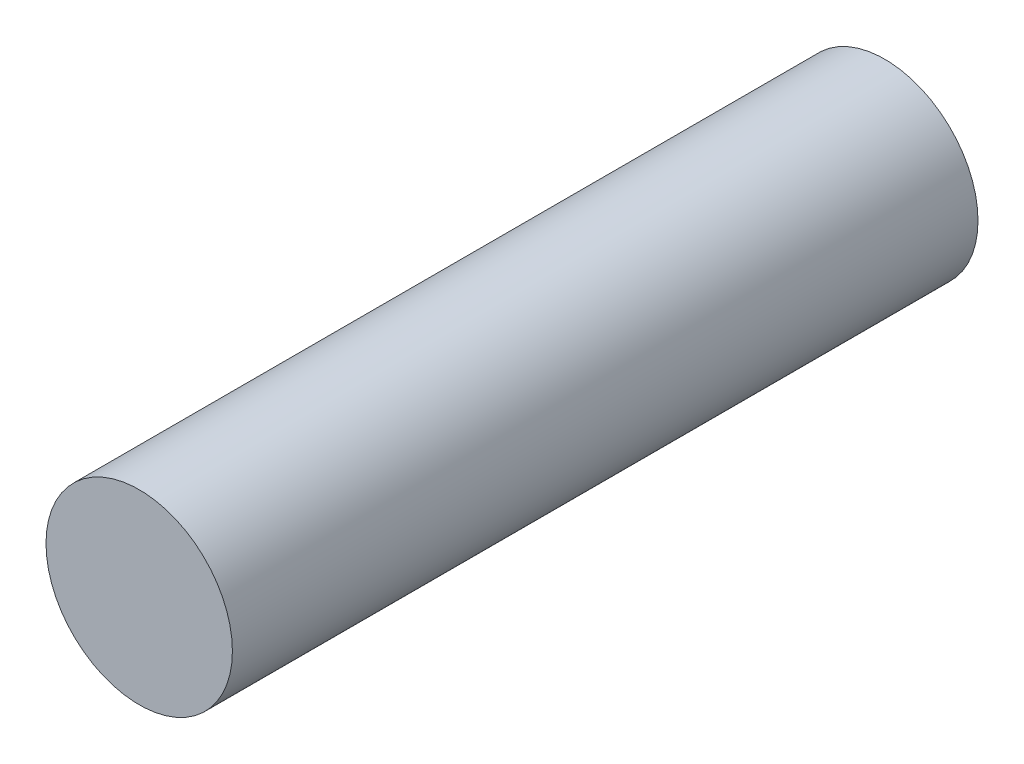
SolidWorks part; units mm, degrees
ref_plane "Front Plane" through (0, 0, 0) normal (0, 0, 1) x (1, 0, 0)
ref_plane "Top Plane" through (0, 0, 0) normal (0, 1, 0) x (1, 0, 0)
ref_plane "Right Plane" through (0, 0, 0) normal (1, 0, 0) x (0, 0, -1)
sketch "Sketch1" plane through (0, 0, 0) normal (0, 0, 1) x (1, 0, 0)
  circle A0 centre (0, 0) radius 3.175
  dimension "D1" = 6.35
extrude "Boss-Extrude1" add sketch "Sketch1" along normal blind 25.4 contours A0
equation "\"Do\"= 0.25"
equation "\"Di\"=0.125"
equation "\"L1\"= 1"
equation "\"t\"= 0.9375 / ( 2 * \"Do\" * 1000 )"
equation "\"ODo\"= ( 2 * \"t\" ) + \"Do\""
equation "\"ODi\"= ( 2 * \"t\" ) + \"Di\""
equation "\"D1@Sketch1\"=\"Do\""
equation "\"D1@Boss-Extrude1\"= \"L1\""
